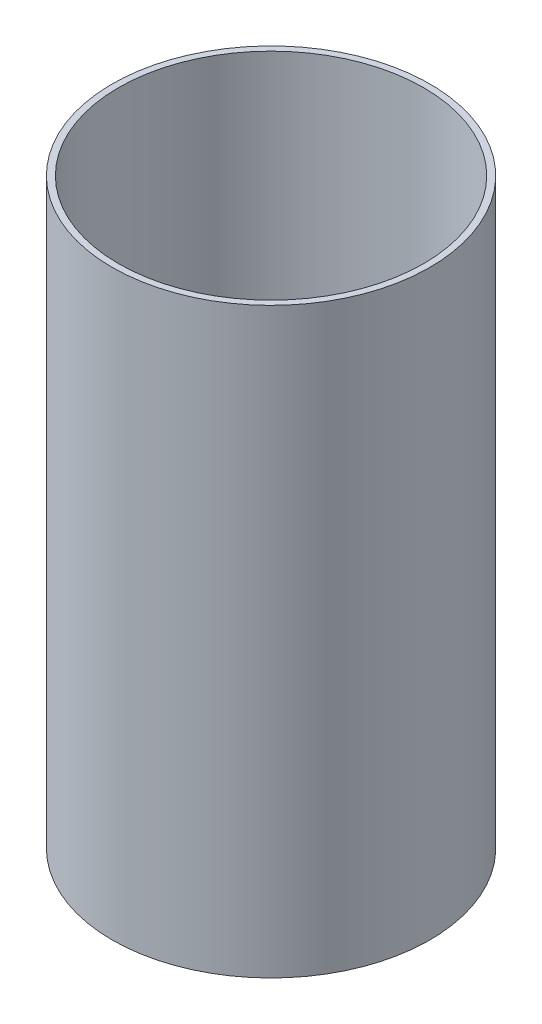
SolidWorks part; units mm, degrees
ref_plane "Front Plane" through (0, 0, 0) normal (0, 0, 1) x (1, 0, 0)
ref_plane "Top Plane" through (0, 0, 0) normal (0, 1, 0) x (1, 0, 0)
ref_plane "Right Plane" through (0, 0, 0) normal (1, 0, 0) x (0, 0, -1)
sketch "Sketch1" plane through (0, 0, 0) normal (0, 1, 0) x (1, 0, 0)
  circle A0 centre (0, 0) radius 38.1
  circle A1 centre (0, 0) radius 36.576
  point P4 (0, 0)
  dimension "D1" = 76.2
  dimension "D2" = 73.152
extrude "Boss-Extrude1" add sketch "Sketch1" along normal mid plane 139.7
equation "\"ATSBayInnerDiameter\"=2.88"
equation "\"ATSBayLength\"=5.5"
equation "\"ATSBandLength\"=1"
equation "\"ATSCouplerOuter\"=\"airframeInnerDiameter\""
equation "\"ATSOffsetFromAft\"=1.5"
equation "\"airframeInnerDiameter\"=3"
equation "\"D1@Sketch1\"=\"airframeInnerDiameter\""
equation "\"D2@Sketch1\"=\"ATSBayInnerDiameter\""
equation "\"D1@Boss-Extrude1\"=\"ATSBayLength\""
